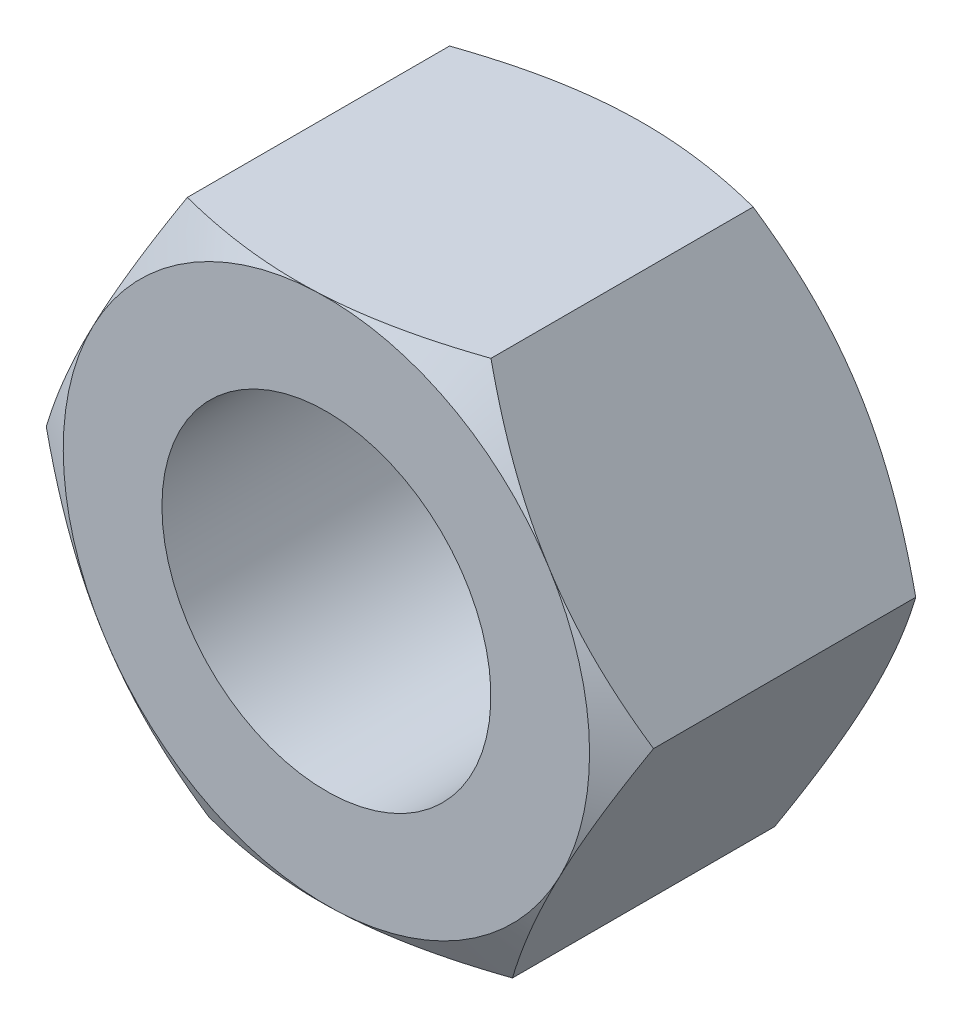
SolidWorks part; units mm, degrees
ref_plane "Front Plane" through (0, 0, 0) normal (0, 0, 1) x (1, 0, 0)
ref_plane "Top Plane" through (0, 0, 0) normal (0, 1, 0) x (1, 0, 0)
ref_plane "Right Plane" through (0, 0, 0) normal (1, 0, 0) x (0, 0, -1)
sketch "Sketch1" plane through (0, 0, 0) normal (0, 0, 1) x (1, 0, 0)
  line L1 (2.144, 4.0911) -> (-2.471, 3.9023)
  line L2 (-2.471, 3.9023) -> (-4.6149, -0.1888)
  line L3 (-4.6149, -0.1888) -> (-2.144, -4.0911)
  line L4 (-2.144, -4.0911) -> (2.471, -3.9023)
  line L5 (2.471, -3.9023) -> (4.6149, 0.1888)
  line L6 (4.6149, 0.1888) -> (2.144, 4.0911)
  circle A0 centre (0, 0) radius 4 construction
  dimension "D1" = 8
extrude "Boss-Extrude1" add sketch "Sketch1" along normal blind 4.7
sketch "Sketch2" plane through (0, 0, 4.7) normal (0, 0, 1) x (1, 0, 0)
  circle A0 centre (0, 0) radius 4
extrude "Cut-Extrude1" cut sketch "Sketch2" against normal blind 4.7 draft 60 flip side to cut
sketch "Sketch3" plane through (0, 0, 0) normal (0, 0, -1) x (-1, 0, 0)
  circle A0 centre (0, 0) radius 4
extrude "Cut-Extrude2" cut sketch "Sketch3" against normal blind 4.7 draft 60 flip side to cut
sketch "Sketch4" plane through (0, 0, 0) normal (0, 0, -1) x (-1, 0, 0)
  circle A0 centre (0, 0) radius 2.5
  dimension "D1" = 5
extrude "Cut-Extrude3" cut sketch "Sketch4" against normal through all
sketch "Sketch5" plane through (0, 0, 0) normal (0, 0, -1) x (-1, 0, 0)
  circle A0 centre (0, 0) radius 2.5 construction
  circle A1 centre (0, 0) radius 2.5
ref_plane "Plane1" through (-2.5, 0, 0) normal (1, 0, 0) x (0, 0, -1)
